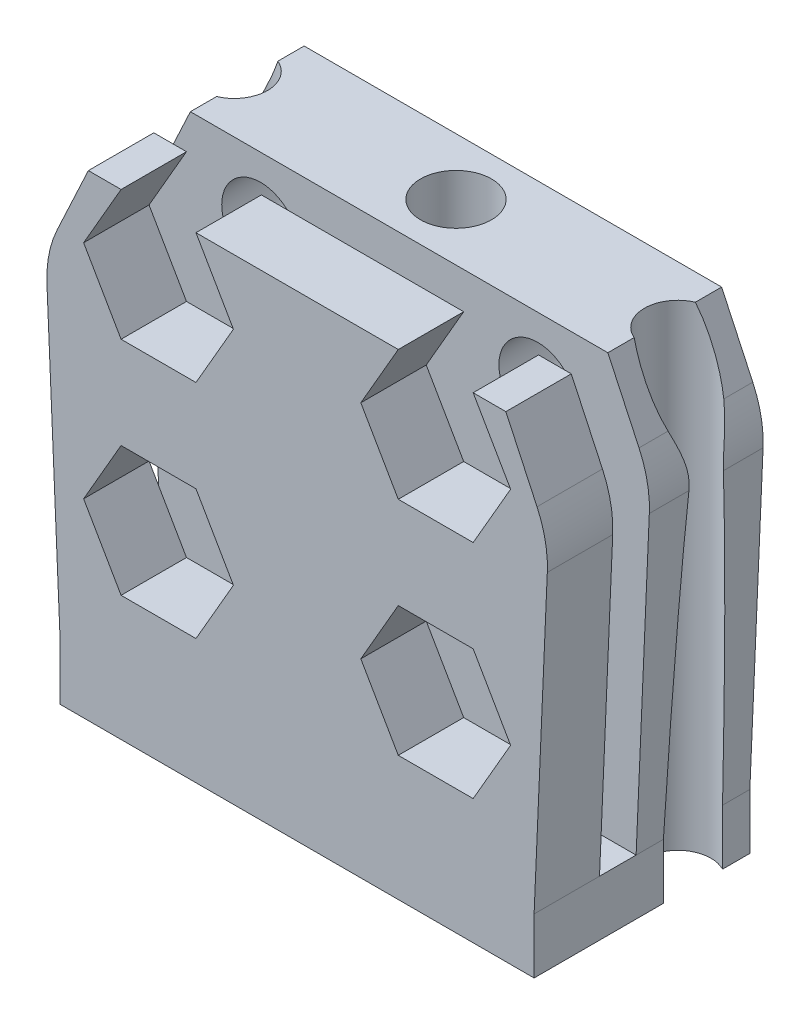
SolidWorks part; units mm, degrees
ref_plane "Front Plane" through (0, 0, 0) normal (0, 0, 1) x (1, 0, 0)
ref_plane "Top Plane" through (0, 0, 0) normal (0, 1, 0) x (1, 0, 0)
ref_plane "Right Plane" through (0, 0, 0) normal (1, 0, 0) x (0, 0, -1)
sketch "Sketch1" plane through (0, 0, 0) normal (0, 0, 1) x (1, 0, 0)
  line L0 (-10.6869, 72.9419) -> (10.6869, 72.9419)
  line L1 (-16.5368, 72.9419) -> (10.0115, 72.9419) construction
  line L9 (8.1815, 15.5604) -> (11.2824, 86.5808)
  line L10 (10.8187, 88.912) -> (7.7036, 95.5923)
  line L11 (-7.7036, 95.5923) -> (-10.8187, 88.912)
  line L12 (-11.2824, 86.5808) -> (-8.1815, 15.5604)
  line L13 (-12.9793, 4.4071) -> (-12.1223, -7.8488)
  line L14 (-11.0475, -10.6126) -> (-8.2635, -14.1126)
  line L15 (-4.3504, -16) -> (4.3504, -16)
  line L16 (8.2635, -14.1126) -> (11.0475, -10.6126)
  line L17 (12.1223, -7.8488) -> (12.9793, 4.4071)
  line L18 (8.1815, 15.5604) -> (11.2824, 86.5808)
  line L19 (10.8187, 88.912) -> (7.7036, 95.5923)
  line L20 (-7.7036, 95.5923) -> (-10.8187, 88.912)
  line L21 (-11.2824, 86.5808) -> (-8.1815, 15.5604)
  line L22 (-12.9793, 4.4071) -> (-12.1223, -7.8488)
  line L23 (-11.0475, -10.6126) -> (-8.2635, -14.1126)
  line L24 (-4.3504, -16) -> (4.3504, -16)
  line L25 (8.2635, -14.1126) -> (11.0475, -10.6126)
  line L26 (12.1223, -7.8488) -> (12.9793, 4.4071)
  circle A0 centre (6.25, 79) radius 1.5 construction
  circle A1 centre (6.25, 79) radius 1.5
  circle A2 centre (-6.25, 79) radius 1.5 construction
  circle A3 centre (-6.25, 79) radius 1.5
  circle A4 centre (-6.25, 89) radius 1.5 construction
  circle A5 centre (-6.25, 89) radius 1.5
  circle A6 centre (6.25, 89) radius 1.5 construction
  circle A7 centre (6.25, 89) radius 1.5
  arc A11 (8.1815, 15.5604) -> (9.9632, 11.5118) centre (13.1768, 15.3423) ccw
  arc A12 (11.2824, 86.5808) -> (10.8187, 88.912) centre (6.2871, 86.7989) ccw
  arc A13 (7.7036, 95.5923) -> (-7.7036, 95.5923) centre (0, 92) ccw
  arc A14 (-10.8187, 88.912) -> (-11.2824, 86.5808) centre (-6.2871, 86.7989) ccw
  arc A15 (-9.9632, 11.5118) -> (-8.1815, 15.5604) centre (-13.1768, 15.3423) ccw
  arc A16 (-9.9632, 11.5118) -> (-12.9793, 4.4071) centre (-4.5, 5) ccw
  arc A17 (-12.1223, -7.8488) -> (-11.0475, -10.6126) centre (-7.1345, -7.5) ccw
  arc A18 (-8.2635, -14.1126) -> (-4.3504, -16) centre (-4.3504, -11) ccw
  arc A19 (4.3504, -16) -> (8.2635, -14.1126) centre (4.3504, -11) ccw
  arc A20 (11.0475, -10.6126) -> (12.1223, -7.8488) centre (7.1345, -7.5) ccw
  arc A21 (12.9793, 4.4071) -> (9.9632, 11.5118) centre (4.5, 5) ccw
  arc A22 (8.1815, 15.5604) -> (9.9632, 11.5118) centre (13.1768, 15.3423) ccw
  arc A23 (11.2824, 86.5808) -> (10.8187, 88.912) centre (6.2871, 86.7989) ccw
  arc A24 (7.7036, 95.5923) -> (-7.7036, 95.5923) centre (0, 92) ccw
  arc A25 (-10.8187, 88.912) -> (-11.2824, 86.5808) centre (-6.2871, 86.7989) ccw
  arc A26 (-9.9632, 11.5118) -> (-8.1815, 15.5604) centre (-13.1768, 15.3423) ccw
  arc A27 (-9.9632, 11.5118) -> (-12.9793, 4.4071) centre (-4.5, 5) ccw
  arc A28 (-12.1223, -7.8488) -> (-11.0475, -10.6126) centre (-7.1345, -7.5) ccw
  arc A29 (-8.2635, -14.1126) -> (-4.3504, -16) centre (-4.3504, -11) ccw
  arc A30 (4.3504, -16) -> (8.2635, -14.1126) centre (4.3504, -11) ccw
  arc A31 (11.0475, -10.6126) -> (12.1223, -7.8488) centre (7.1345, -7.5) ccw
  arc A32 (12.9793, 4.4071) -> (9.9632, 11.5118) centre (4.5, 5) ccw
  dimension "D1" = 0
extrude "Boss-Extrude1" add sketch "Sketch1" along normal blind 5.13 contours L20 A25 L21 L0 L18 A23 L19 A24 A1 A3 A5 A7
sketch "Sketch2" plane through (0, 72.9419, 0) normal (0, -1, 0) x (1, 0, 0)
  line L4 (-10.6869, 0) -> (10.6869, 0)
  line L5 (10.6869, 0) -> (10.6869, 5.13)
  line L6 (10.6869, 5.13) -> (-10.6869, 5.13)
  line L7 (-10.6869, 5.13) -> (-10.6869, 0)
  line L8 (-10.6869, 0) -> (10.6869, 0)
  line L9 (10.6869, 0) -> (10.6869, 5.13)
  line L10 (10.6869, 5.13) -> (-10.6869, 5.13)
  line L11 (-10.6869, 5.13) -> (-10.6869, 0)
  dimension "D1" = 0
extrude "Boss-Extrude2" add sketch "Sketch2" along normal blind 2.5
sketch "Sketch3" plane through (0, 0, 5.13) normal (0, 0, 1) x (1, 0, 0)
  line L1 (-10.6869, 72.9419) -> (10.6869, 72.9419)
  line L2 (-10.6869, 72.9419) -> (-10.6869, 70.4419)
  line L3 (-10.6869, 70.4419) -> (10.6869, 70.4419)
  line L4 (10.6869, 72.9419) -> (10.6869, 70.4419)
extrude "Boss-Extrude3" add sketch "Sketch3" along normal blind 4.6
sketch "Sketch4" plane through (0, 0, 9.73) normal (0, 0, 1) x (1, 0, 0)
  line L0 (-6.25, 89) -> (-2.8725, 89) construction
  line L1 (-2.8725, 89) -> (-4.5613, 91.925)
  line L2 (-4.5613, 91.925) -> (-7.9387, 91.925)
  line L3 (-7.9387, 91.925) -> (-9.6275, 89)
  line L4 (-9.6275, 89) -> (-7.9387, 86.075)
  line L5 (-10.6869, 72.9419) -> (10.6869, 72.9419)
  line L6 (10.6869, 72.9419) -> (11.2824, 86.5808)
  line L7 (10.8187, 88.912) -> (7.7036, 95.5923)
  line L8 (-7.7036, 95.5923) -> (-10.8187, 88.912)
  line L9 (-11.2824, 86.5808) -> (-10.6869, 72.9419)
  line L10 (-10.6869, 72.9419) -> (10.6869, 72.9419)
  line L11 (10.6869, 72.9419) -> (11.2824, 86.5808)
  line L12 (10.8187, 88.912) -> (7.7036, 95.5923)
  line L13 (-7.7036, 95.5923) -> (-10.8187, 88.912)
  line L14 (-11.2824, 86.5808) -> (-10.6869, 72.9419)
  line L15 (-7.9387, 86.075) -> (-4.5613, 86.075)
  line L16 (-4.5613, 86.075) -> (-2.8725, 89)
  line L17 (6.25, 89) -> (2.8725, 89) construction
  line L18 (2.8725, 89) -> (4.5613, 86.075)
  line L19 (4.5613, 86.075) -> (7.9387, 86.075)
  line L20 (7.9387, 86.075) -> (9.6275, 89)
  line L21 (9.6275, 89) -> (7.9387, 91.925)
  line L22 (7.9387, 91.925) -> (4.5613, 91.925)
  line L23 (4.5613, 91.925) -> (2.8725, 89)
  line L24 (-6.25, 79) -> (-2.8725, 79) construction
  line L25 (-2.8725, 79) -> (-4.5613, 81.925)
  line L26 (-4.5613, 81.925) -> (-7.9387, 81.925)
  line L27 (-7.9387, 81.925) -> (-9.6275, 79)
  line L28 (-9.6275, 79) -> (-7.9387, 76.075)
  line L29 (-7.9387, 76.075) -> (-4.5613, 76.075)
  line L30 (-4.5613, 76.075) -> (-2.8725, 79)
  line L31 (6.25, 79) -> (2.8725, 79) construction
  line L32 (9.6275, 79) -> (7.9387, 81.925)
  line L33 (7.9387, 81.925) -> (4.5613, 81.925)
  line L34 (4.5613, 81.925) -> (2.8725, 79)
  line L35 (2.8725, 79) -> (4.5613, 76.075)
  line L36 (4.5613, 76.075) -> (7.9387, 76.075)
  line L37 (7.9387, 76.075) -> (9.6275, 79)
  line L38 (9.6275, 89) -> (-9.6275, 89)
  line L39 (-9.6275, 89) -> (-10.7776, 89)
  line L40 (9.6275, 89) -> (10.7776, 89)
  line L41 (-4.5613, 91.925) -> (4.5613, 91.925)
  line L43 (7.9387, 91.925) -> (9.4137, 91.925)
  line L44 (-7.9387, 91.925) -> (-9.4137, 91.925)
  circle A0 centre (6.25, 89) radius 1.5 construction
  circle A1 centre (-6.25, 89) radius 1.5 construction
  circle A2 centre (-6.25, 79) radius 1.5 construction
  arc A3 (11.2824, 86.5808) -> (10.8187, 88.912) centre (6.2871, 86.7989) ccw
  arc A4 (7.7036, 95.5923) -> (-7.7036, 95.5923) centre (0, 92) ccw
  arc A5 (-10.8187, 88.912) -> (-11.2824, 86.5808) centre (-6.2871, 86.7989) ccw
  arc A6 (11.2824, 86.5808) -> (10.8187, 88.912) centre (6.2871, 86.7989) ccw
  arc A7 (7.7036, 95.5923) -> (-7.7036, 95.5923) centre (0, 92) ccw
  arc A8 (-10.8187, 88.912) -> (-11.2824, 86.5808) centre (-6.2871, 86.7989) ccw
  circle A9 centre (6.25, 79) radius 1.5 construction
  circle A10 centre (6.25, 89) radius 1.5
  circle A11 centre (-6.25, 89) radius 1.5
  circle A12 centre (-6.25, 79) radius 1.5
  circle A13 centre (6.25, 79) radius 1.5
  circle A14 centre (-6.25, 89) radius 2.925 construction
  circle A15 centre (6.25, 89) radius 2.925 construction
  circle A16 centre (-6.25, 79) radius 2.925 construction
  circle A17 centre (6.25, 79) radius 2.925 construction
  dimension "D2" = 5.85
  dimension "D1" = 0
extrude "Boss-Extrude4" add sketch "Sketch4" against normal offset from surface (2.95 mm away) 1.65
sketch "Sketch5" plane through (0, 0, 0) normal (0, 0, -1) x (-1, 0, 0)
  circle A0 centre (-6.25, 89) radius 1.75
  circle A1 centre (6.25, 89) radius 1.75
  circle A2 centre (6.25, 79) radius 1.75
  circle A3 centre (-6.25, 79) radius 1.75
  dimension "D1" = 3.5
extrude "Cut-Extrude1" cut sketch "Sketch5" against normal up to next
sketch "Sketch6" plane through (0, 70.4419, 0) normal (0, -1, 0) x (1, 0, 0)
  line L0 (-10.6869, 2.565) -> (10.6869, 2.565) construction
  line L1 (-10.6869, 9.73) -> (-10.6869, 0) construction
  line L2 (10.6869, 0) -> (10.6869, 9.73) construction
  line L3 (-10.6869, 5.13) -> (-10.6869, 0) construction
  line L4 (0, 0) -> (0, 9.73) construction
  line L5 (-10.6869, 9.73) -> (10.6869, 9.73) construction
  circle A0 centre (0, 2.565) radius 1.6
  circle A1 centre (-10, 2.565) radius 1.5
  circle A2 centre (10, 2.565) radius 1.5
  dimension "D1" = 3.2
  dimension "D3" = 3
  dimension "D2" = 10
extrude "Cut-Extrude2" cut sketch "Sketch6" against normal through all
sketch "Sketch7" plane through (0, 0, 5.13) normal (0, 0, 1) x (1, 0, 0)
  line L0 (-9.4137, 91.925) -> (9.4137, 91.925)
  line L1 (-6.25, 89) -> (-4.5, 89) construction
  line L2 (-4.5613, 91.925) -> (4.5613, 91.925) construction
  line L5 (-10.6869, 72.9419) -> (10.6869, 72.9419)
  line L6 (10.6869, 72.9419) -> (11.2824, 86.5808)
  line L7 (10.8187, 88.912) -> (7.7036, 95.5923)
  line L8 (-7.7036, 95.5923) -> (-10.8187, 88.912)
  line L9 (-11.2824, 86.5808) -> (-10.6869, 72.9419)
  line L10 (-10.6869, 72.9419) -> (10.6869, 72.9419)
  line L11 (10.6869, 72.9419) -> (11.2824, 86.5808)
  line L12 (10.8187, 88.912) -> (7.7036, 95.5923)
  line L13 (-7.7036, 95.5923) -> (-10.8187, 88.912)
  line L14 (-11.2824, 86.5808) -> (-10.6869, 72.9419)
  circle A0 centre (-6.25, 89) radius 1.75 construction
  arc A3 (11.2824, 86.5808) -> (10.8187, 88.912) centre (6.2871, 86.7989) ccw
  arc A4 (7.7036, 95.5923) -> (-7.7036, 95.5923) centre (0, 92) ccw
  arc A5 (-10.8187, 88.912) -> (-11.2824, 86.5808) centre (-6.2871, 86.7989) ccw
  arc A6 (11.2824, 86.5808) -> (10.8187, 88.912) centre (6.2871, 86.7989) ccw
  arc A7 (7.7036, 95.5923) -> (-7.7036, 95.5923) centre (0, 92) ccw
  arc A8 (-10.8187, 88.912) -> (-11.2824, 86.5808) centre (-6.2871, 86.7989) ccw
  line M16 (10.8187, 88.912) -> (7.7036, 95.5923)
  arc M17 (7.7036, 95.5923) -> (-7.7036, 95.5923) centre (0, 92) ccw
  line M18 (-7.7036, 95.5923) -> (-10.8187, 88.912)
  dimension "D1" = 0
extrude "Cut-Extrude3" cut sketch "Sketch7" against normal up to next contours L0 M18 M16 M17
